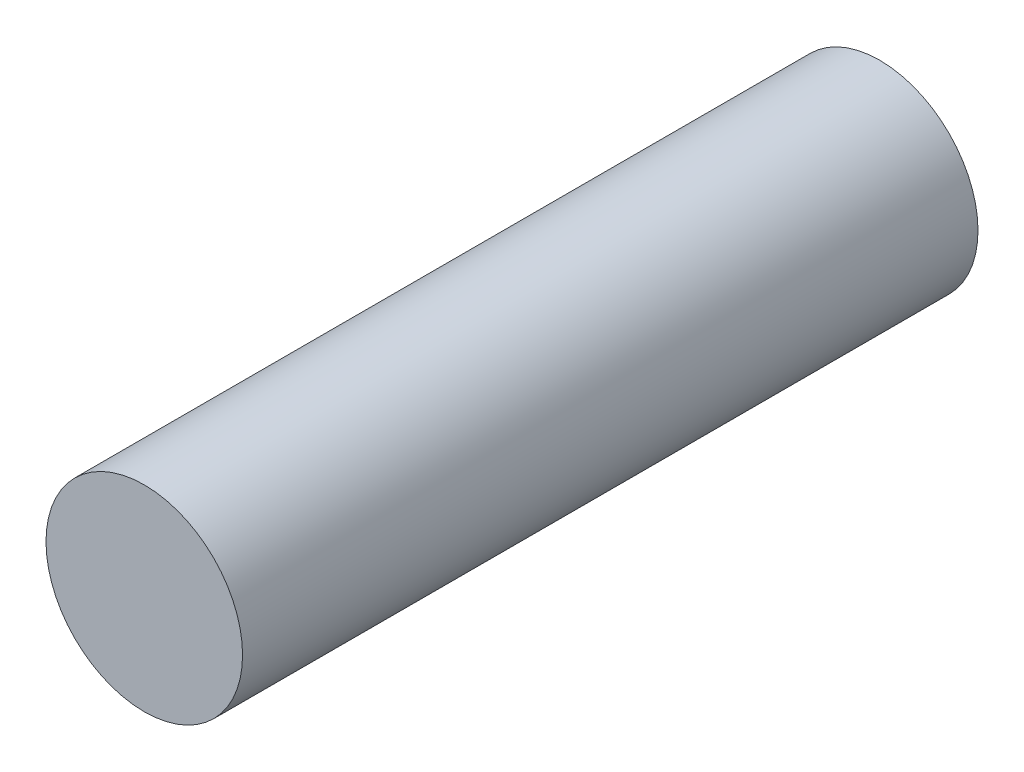
SolidWorks part; units mm, degrees
ref_plane "Front Plane" through (0, 0, 0) normal (0, 0, 1) x (1, 0, 0)
ref_plane "Top Plane" through (0, 0, 0) normal (0, 1, 0) x (1, 0, 0)
ref_plane "Right Plane" through (0, 0, 0) normal (1, 0, 0) x (0, 0, -1)
sketch "Sketch1" plane through (0, 0, 0) normal (0, 0, 1) x (1, 0, 0)
  circle A0 centre (0, 0) radius 0.89
  dimension "D1" = 1.78
extrude "Boss-Extrude1" add sketch "Sketch1" along normal blind 6.66
